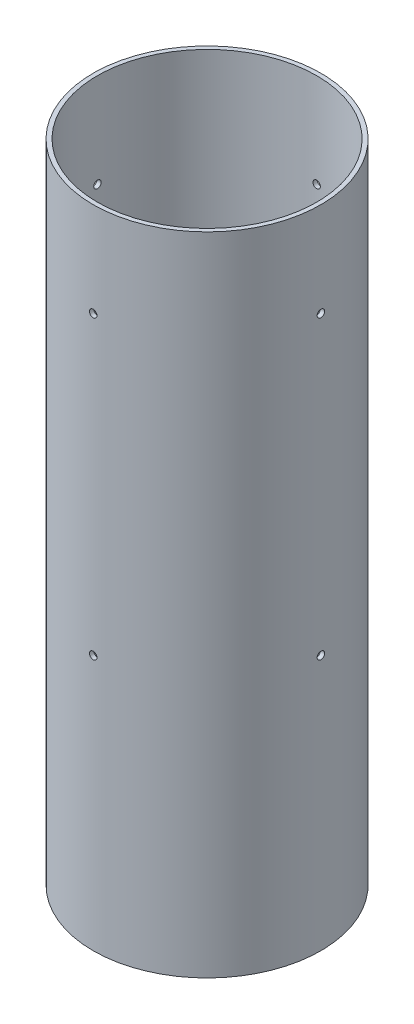
SolidWorks part; units mm, degrees
material "E-Glass Fiber"
ref_plane "Front Plane" through (0, 0, 0) normal (0, 0, 1) x (1, 0, 0)
ref_plane "Top Plane" through (0, 0, 0) normal (0, 1, 0) x (1, 0, 0)
ref_plane "Right Plane" through (0, 0, 0) normal (1, 0, 0) x (0, 0, -1)
sketch "Sketch1" plane through (0, 0, 0) normal (0, 1, 0) x (1, 0, 0)
  circle A0 centre (0, 0) radius 53.721
  circle A1 centre (0, 0) radius 51.7271
  dimension "D1" = 107.442
  dimension "D2" = 103.4542
extrude "Boss-Extrude1" add sketch "Sketch1" along normal blind 304.8
sketch "Sketch2" plane through (0, 0, 0) normal (0, 0, 1) x (1, 0, 0)
  line L2 (0, 0) -> (0, 120.65)
  circle A0 centre (0, 120.65) radius 1.7526
  dimension "D2" = 3.5052
  dimension "D1" = 120.65
extrude "Bulkhead Holes" cut sketch "Sketch2" against normal blind 127 contours A0
pattern_circular "CirPattern1" count 4 over 360 about axis through (0, 304.8, 0) along (0, -1, 0) of "Bulkhead Holes"
ref_plane "Plane1" through (53.721, 0, 0) normal (1, 0, 0) x (0, 0, -1)
sketch "Sketch3" plane through (53.721, 0, 0) normal (1, 0, 0) x (0, 0, -1)
  line L0 (0, 0) -> (0, 304.8) construction
  line L1 (-53.721, 0) -> (53.721, 0) construction
  line L2 (51.7271, 304.8) -> (-51.7271, 304.8) construction
  line L3 (53.721, 304.8) -> (-53.721, 304.8) construction
  circle A0 centre (0, 260.35) radius 1.7526
  dimension "D1" = 3.5052
  dimension "D2" = 44.45
extrude "Cut-Extrude1" cut sketch "Sketch3" against normal up to next
pattern_circular "CirPattern2" count 4 over 360 about axis through (0, 304.8, 0) along (0, -1, 0) of "Cut-Extrude1"
